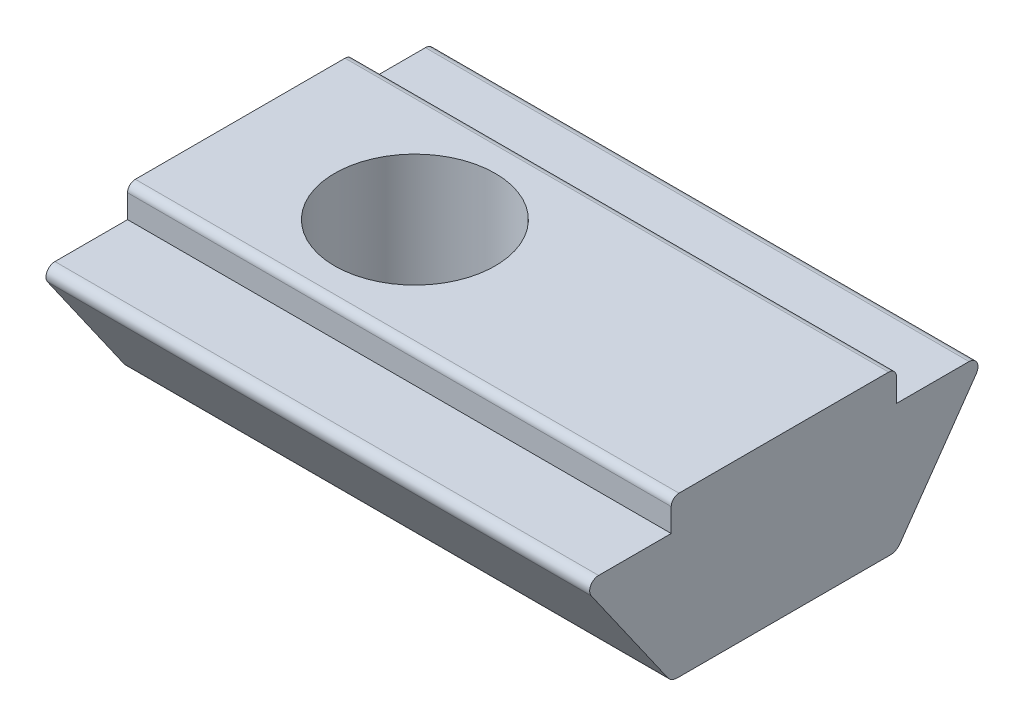
SolidWorks part; units mm, degrees
ref_plane "Front Plane" through (0, 0, 0) normal (0, 0, 1) x (1, 0, 0)
ref_plane "Top Plane" through (0, 0, 0) normal (0, 1, 0) x (1, 0, 0)
ref_plane "Right Plane" through (0, 0, 0) normal (1, 0, 0) x (0, 0, -1)
ref_plane "Plane1" through (-4.5, 0, 0) normal (1, 0, 0) x (0, 0, -1)
ref_plane "Plane2" through (6, 0, 0) normal (1, 0, 0) x (0, 0, -1)
sketch "Sketch1" plane through (-4.5, 0, 0) normal (1, 0, 0) x (0, 0, -1)
  line L0 (2.9, 0) -> (-2.9, 0)
  line L1 (-2.9, 0) -> (-2.9, -0.8)
  line L2 (-2.9, -0.8) -> (-4.77, -0.8)
  line L3 (5, 0) -> (5, -4.1) construction
  line L4 (-4.9584, -1.162) -> (-2.9, -4.1)
  line L5 (-2.9, -4.1) -> (2.9, -4.1)
  line L6 (2.9, -4.1) -> (4.9584, -1.162)
  line L7 (-5, 0) -> (-5, -4.1) construction
  line L8 (4.77, -0.8) -> (2.9, -0.8)
  line L9 (2.9, -0.8) -> (2.9, 0)
  line L10 (0, 0) -> (0, -4.1) construction
  arc A2 (-4.9584, -1.162) -> (-4.77, -0.8) centre (-4.77, -1.03) cw
  arc A3 (4.9584, -1.162) -> (4.77, -0.8) centre (4.77, -1.03) ccw
  point P18 (-2.9, -4.1)
  point P21 (2.9, -4.1)
  dimension "FIX_4" = 0.23
  dimension "FIX_1" = 10
  dimension "FIX_2" = 5.8
  dimension "T" = 4.1
  dimension "FIX_3" = 3.3
  dimension "FIX_5" = 5.8
extrude "Boss-Extrude1" add sketch "Sketch1" along normal blind 14
fillet "Fillet1" radius 0.3 2 edges at (2.5, -4.1, 2.9) (2.5, -4.1, -2.9)
fillet "Fillet2" radius 0.2 2 edges at (2.5, 0, 2.9) (2.5, 0, -2.9)
sketch "Sketch2" plane through (6, 0, 0) normal (1, 0, 0) x (0, 0, -1)
  line L0 (0, 1.6655) -> (0, -9.505) construction
  line L2 (0, -3.9) -> (2.1, -3.9)
  line L3 (0, -3.9) -> (0, -4.1)
  line L4 (0, -4.1) -> (2.1, -4.1)
  line L5 (2.1, -3.9) -> (2.1, -4.1)
  dimension "FIX_10" = 0.2
  dimension "FIX_9" = 2.1
  dimension "T" = 4.1
revolve "Cut-Revolve1" cut sketch "Sketch2" angle 360 about L0
sketch "Sketch3" plane through (6, 0, 0) normal (1, 0, 0) x (0, 0, -1)
  line L0 (0, 0) -> (0, -4.8) construction
  line L1 (1.6703, -3.9) -> (0, -3.9) construction
  line L2 (1.6703, -4.8) -> (0, -4.8) construction
  line L3 (1.6703, -3.9) -> (0, -3.9)
  line L4 (0, -3.9) -> (0, -4.8)
  arc A0 (0, -4.8) -> (1.6703, -3.9) centre (0, -2.8) ccw
  dimension "FIX_12" = 4
  dimension "KSS_1" = 4.8
  dimension "KSS_2" = 3.9
revolve "Revolve1" add sketch "Sketch3" angle 360 about L0
hole_wizard "Tapped Hole1" positions "Sketch5" profile "Sketch4" tap size "M5x0.8" standard "JIS" end condition through all
sketch "Sketch5" plane through (0, 0, 0) normal (0, 1, 0) x (1, 0, 0)
  point P0 (0, 0)
cosmetic thread "Thread1" parameters "NFIX_1"=5
sketch "Sketch4" plane through (0, 0, 0) normal (1, 0, 0) x (0, 0, 1)
  line L0 (0, 0) -> (0, 4.8)
  line L1 (0, 4.8) -> (2.067, 4.8)
  line L2 (2.067, 4.8) -> (2.067, 0)
  line L5 (2.067, 0) -> (0, 0)
  line L11 (0, 0) -> (0, 4.8) construction
  dimension "Thru Tap Drill Dia." = 4.134
  dimension "Thru Tap Drill Depth" = 4.8
equation "\"KSS_1@Sketch3\" = \"T@Sketch1\" + 0.7"
equation "\"KSS_2@Sketch3\"= \"T@Sketch1\" - 0.2"
